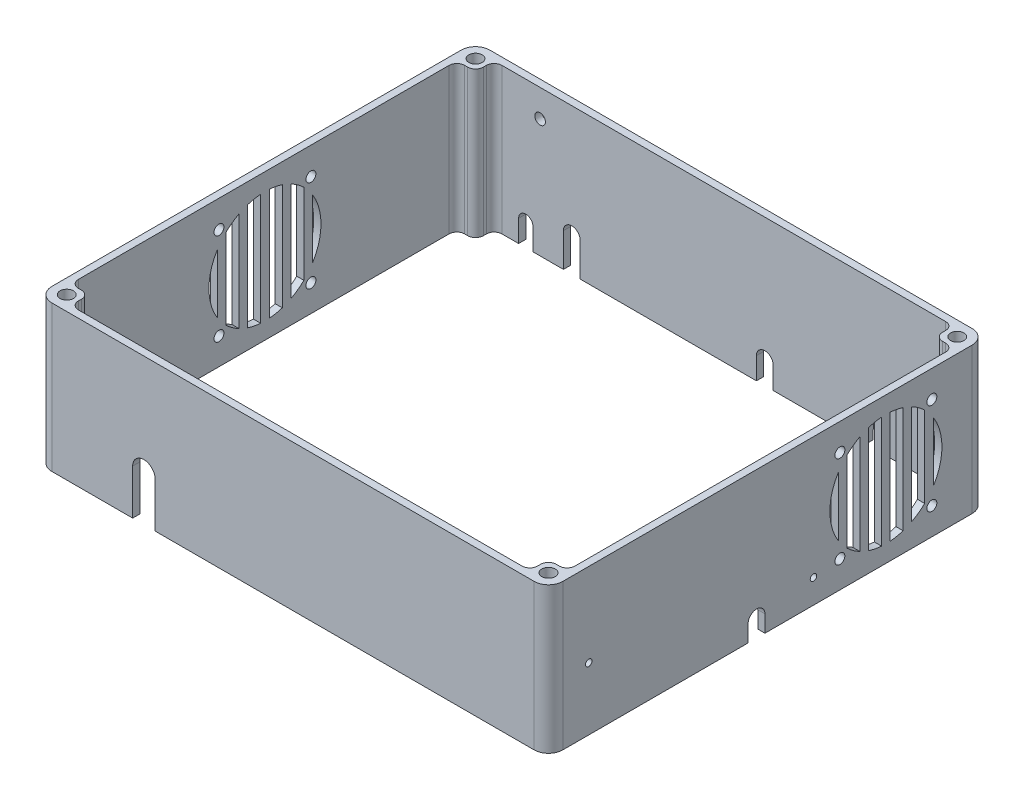
SolidWorks part; units mm, degrees
other "Markup1"
sketch "Sketch20" plane through (177.8, 5.08, 6.35) normal (0.2164, -0.9756, 0.0368) x (0.7593, 0.1445, -0.6344)
material "ABS"
ref_plane "Front Plane" through (0, 0, 0) normal (0, 0, 1) x (1, 0, 0)
ref_plane "Top Plane" through (0, 0, 0) normal (0, 1, 0) x (1, 0, 0)
ref_plane "Right Plane" through (0, 0, 0) normal (1, 0, 0) x (0, 0, -1)
sketch "Sketch1" plane through (0, 0, 0) normal (0, 1, 0) x (1, 0, 0)
  line L2 (0, 0) -> (0, 146.05)
  line L3 (0, 146.05) -> (177.8, 146.05)
  line L4 (177.8, 0) -> (177.8, 146.05)
  line L6 (0, 0) -> (0, -6.35)
  line L7 (0, -6.35) -> (177.8, -6.35)
  line L8 (177.8, 0) -> (177.8, -6.35)
  dimension "D1" = 146.05
  dimension "D2" = 177.8
  dimension "D3" = 6.35
extrude "Boss-Extrude1" add sketch "Sketch1" along normal blind 55.88 contours L2 L3 L4 L8 L7 L6
shell "Shell1" thickness 2.5
sketch "Sketch3" plane through (0, 55.88, 0) normal (0, 1, 0) x (1, 0, 0)
  line L1 (2.5, 143.55) -> (9, 143.55)
  line L2 (2.5, 143.55) -> (2.5, 137.05)
  line L3 (2.5, 137.05) -> (9, 137.05)
  line L4 (9, 143.55) -> (9, 137.05)
  line L5 (175.3, 143.55) -> (168.8, 143.55)
  line L6 (175.3, 143.55) -> (175.3, 137.05)
  line L7 (175.3, 137.05) -> (168.8, 137.05)
  line L8 (168.8, 143.55) -> (168.8, 137.05)
  line L9 (175.3, -3.85) -> (168.8, -3.85)
  line L10 (175.3, -3.85) -> (175.3, 2.65)
  line L11 (175.3, 2.65) -> (168.8, 2.65)
  line L12 (168.8, -3.85) -> (168.8, 2.65)
  line L13 (2.5, -3.85) -> (9, -3.85)
  line L14 (2.5, -3.85) -> (2.5, 2.65)
  line L15 (2.5, 2.65) -> (9, 2.65)
  line L16 (9, -3.85) -> (9, 2.65)
  line L19 (2.5, -3.85) -> (175.3, -3.85) construction
  dimension "D1" = 6.5
  dimension "D2" = 6.5
extrude "Boss-Extrude2" add sketch "Sketch3" against normal up to surface (53.38 mm away) up to face at (88.9, 2.5, -69.85)
sketch "pi&pcbSketch"
  dimension "D1" = 58
  dimension "D2" = 48.9998
  dimension "D3" = 4.826
  dimension "D4" = 12.192
  dimension "D5" = 4.6482
  dimension "D6" = 4.826
  dimension "D7" = 3.0734
  dimension "D8" = 12.954
  dimension "D9" = 13.8684
sketch "bottomHoleSketch" [suppressed] plane through (0, 0, -5.08) normal (0, 1, 0) x (-1, 0, 0)
  line L0 (0, -140.97) -> (-177.8, -140.97) construction
  line L1 (-177.8, -140.97) -> (-177.8, 11.43) construction
  line L2 (0, 11.43) -> (-177.8, 11.43) construction
  line L3 (0, -140.97) -> (0, 11.43) construction
  circle A0 centre (-172.72, 6.35) radius 2.5249
  circle A1 centre (-5.08, 6.35) radius 2.5249
  circle A2 centre (-172.72, -135.89) radius 2.5249
  circle A3 centre (-5.08, -135.89) radius 2.5249
  dimension "D3" = 5.0497
  dimension "D1" = 5.08
  dimension "D2" = 5.08
  dimension "D4" = 5.08
  dimension "D5" = 5.08
sketch "Sketch35" plane through (0, 55.88, -60.96) normal (0, 1, 0) x (-1, 0, 0)
  line L0 (-177.8, -85.09) -> (-177.8, 67.31) construction
  line L1 (0, 67.31) -> (-177.8, 67.31) construction
  line L2 (0, -85.09) -> (0, 67.31) construction
  line L3 (0, -85.09) -> (-177.8, -85.09) construction
  circle A0 centre (-172.72, 62.23) radius 2.325
  circle A1 centre (-5.08, 62.23) radius 2.325
  circle A2 centre (-172.72, -80.01) radius 2.325
  circle A3 centre (-5.08, -80.01) radius 2.325
  dimension "D3" = 4.65
  dimension "D1" = 5.08
  dimension "D2" = 5.08
  dimension "D4" = 5.08
  dimension "D5" = 5.08
extrude "Top holes" cut sketch "Sketch35" against normal blind 10
sketch "Ethernet" plane through (0, 2.5, 0) normal (0, 1, 0) x (1, 0, 0)
  line L1 (132.4077, 54.1476) -> (157.8077, 54.1476)
  line L2 (132.4077, 54.1476) -> (132.4077, 38.2816)
  line L3 (132.4077, 38.2816) -> (157.8077, 38.2816)
  line L4 (157.8077, 54.1476) -> (157.8077, 38.2816)
  dimension "D1" = 25.4
extrude "Ether" [suppressed] add sketch "Ethernet" along normal blind 10.16 separate body
sketch "Sketch9" [suppressed] plane through (0, 0, 6.35) normal (0, 0, 1) x (1, 0, 0)
  line L1 (0, 2.5) -> (177.8, 2.5)
  line L2 (0, 2.5) -> (0, 55.88)
  line L3 (0, 55.88) -> (177.8, 55.88)
  line L4 (177.8, 2.5) -> (177.8, 55.88)
  line L6 (0, 0) -> (177.8, 0) construction
  line L7 (177.8, 55.88) -> (177.8, 0) construction
  line L8 (0, 55.88) -> (0, 0) construction
  dimension "D1" = 2.5
extrude "Cut Top Off" [suppressed] cut sketch "Sketch9" against normal through all
sketch "Sketch7" plane through (0, 2.5, 0) normal (0, 1, 0) x (1, 0, 0)
  circle A0 centre (48.9094, 40.0026) radius 3
  circle A1 centre (106.9094, 40.0026) radius 3
  circle A3 centre (106.9094, 89.0026) radius 3
  circle A4 centre (48.9094, 89.0026) radius 3
  dimension "D1" = 6
  dimension "D4" = 49
  dimension "D2" = 58
extrude "Standoff" [suppressed] add sketch "Sketch7" along normal blind 5
sketch "Sketch10" plane through (0, 0, 6.35) normal (0, 0, 1) x (1, 0, 0)
  line L1 (0, 0) -> (177.8, 0)
  line L2 (0, 0) -> (0, 5.08)
  line L3 (0, 5.08) -> (177.8, 5.08)
  line L4 (177.8, 0) -> (177.8, 5.08)
  dimension "D1" = 5.08
extrude "cut Bottom off" cut sketch "Sketch10" against normal through all
sketch "Sketch17" plane through (0, 5.08, 5.08) normal (0, 1, 0) x (1, 0, 0)
  line L4 (0, 151.13) -> (0, -1.27) construction
  line L5 (0, 151.13) -> (177.8, 151.13) construction
  line L6 (0, -1.27) -> (177.8, -1.27) construction
  line L7 (177.8, 151.13) -> (177.8, -1.27) construction
  circle A0 centre (5.08, 146.05) radius 2.325
  circle A1 centre (172.72, 146.05) radius 2.325
  circle A2 centre (5.08, 3.81) radius 2.325
  circle A3 centre (172.72, 3.81) radius 2.325
  dimension "D3" = 4.65
  dimension "D1" = 5.08
  dimension "D2" = 5.08
  dimension "D4" = 5.08
  dimension "D5" = 5.08
extrude "Bottom of Top holes" cut sketch "Sketch17" along normal blind 10
sketch "Sketch12" plane through (299.72, 0, -143.55) normal (0, 0, 1) x (1, 0, 0)
  line L0 (-121.92, 5.08) -> (-299.72, 5.08) construction
  line L1 (-130.92, 5.08) -> (-130.92, 55.88) construction
  line L2 (-155.3866, 11.684) -> (-155.3866, 5.08)
  line L3 (-155.3866, 5.08) -> (-161.3866, 5.08)
  line L4 (-161.3866, 5.08) -> (-161.2278, 11.7535)
  arc A1 (-155.3866, 11.684) -> (-161.2278, 11.7535) centre (-158.3076, 11.684) ccw
  dimension "D2" = 6.604
  dimension "D1" = 2.921
  dimension "D3" = 24.4666
  dimension "D4" = 6
extrude "cut for Ethernet Cable" cut sketch "Sketch12" against normal up to next
sketch "Sketch15" plane through (0, 0, 3.85) normal (0, 0, -1) x (-1, 0, 0)
  line L0 (-23.749, 10.922) -> (-23.749, 5.08)
  line L1 (-23.749, 5.08) -> (-29.591, 5.08)
  line L2 (-29.591, 5.08) -> (-29.591, 10.922)
  arc A0 (-23.749, 10.922) -> (-29.591, 10.922) centre (-26.67, 10.922) ccw
  dimension "D2" = 2.921
  dimension "D1" = 5.842
  dimension "D3" = 5.842
extrude "usbA" [suppressed] cut sketch "Sketch15" against normal up to next
sketch "Sketch16" plane through (175.3, 0, 0) normal (-1, 0, 0) x (0, 0, 1)
  line L0 (-63.129, 10.922) -> (-63.129, 5.08)
  line L1 (-63.129, 5.08) -> (-68.971, 5.08)
  line L2 (-68.971, 5.08) -> (-68.971, 10.922)
  line L3 (-2.65, 5.08) -> (-137.05, 5.08) construction
  line L4 (-146.05, 55.88) -> (-146.05, 5.08) construction
  arc A0 (-63.129, 10.922) -> (-68.971, 10.922) centre (-66.05, 10.922) ccw
  dimension "D2" = 2.921
  dimension "D1" = 5.842
  dimension "D3" = 5.842
  dimension "D4" = 80
extrude "Keycard" cut sketch "Sketch16" against normal up to next
fillet "Fillet1" radius 2.7 12 edges at (9, 30.48, -2.65) (168.8, 30.48, -2.65) (168.8, 30.48, -137.05) (9, 30.48, -137.05) (2.5, 30.48, -137.05) (9, 30.48, -143.55) (2.5, 30.48, -2.65) (9, 30.48, 3.85) (168.8, 30.48, 3.85) (175.3, 30.48, -2.65) (175.3, 30.48, -137.05) (168.8, 30.48, -143.55)
sketch "Sketch13" plane through (0, 0, -143.55) normal (0, 0, 1) x (1, 0, 0)
  line L4 (106.1, 12.7) -> (106.1, 5.08)
  line L5 (38.9387, 16.76) -> (38.9387, 5.08)
  line L6 (38.9387, 5.08) -> (33.0967, 5.08)
  line L7 (33.0967, 5.08) -> (33.0967, 16.76)
  line L8 (11.7, 5.08) -> (138.3334, 5.08) construction
  line L9 (106.1, 5.08) -> (100.258, 5.08)
  line L10 (177.8, 55.88) -> (177.8, 5.08) construction
  line L12 (100.258, 5.08) -> (100.258, 12.7)
  line L13 (22.5, 12.7) -> (22.5, 5.08)
  line L14 (22.5, 5.08) -> (17.5, 5.08)
  line L15 (17.5, 5.08) -> (17.5, 12.7)
  line L16 (0, 55.88) -> (0, 5.08) construction
  line L17 (11.7, 5.08) -> (138.3334, 5.08) construction
  arc A1 (38.9387, 16.76) -> (33.0967, 16.76) centre (36.0177, 16.76) ccw
  arc A2 (106.1, 12.7) -> (100.258, 12.7) centre (103.179, 12.7) ccw
  arc A3 (22.5, 12.7) -> (17.5, 12.7) centre (20, 12.7) ccw
  dimension "D5" = 2.921
  dimension "D10" = 2.921
  dimension "D12" = 2.5
  dimension "D4" = 5.842
  dimension "D6" = 11.68
  dimension "D8" = 36.0177
  dimension "D9" = 5.842
  dimension "D11" = 5
  dimension "D13" = 7.62
  dimension "D14" = 20
  dimension "D15" = 7.62
  dimension "D16" = 74.621
extrude "usb B" cut sketch "Sketch13" against normal up to next
sketch "Sketch23" plane through (177.8, 0, -323.85) normal (-1, 0, 0) x (0, 0, 1)
  line L89 (177.8, 55.88) -> (177.8, 5.08) construction
  line L121 (177.8, 30.48) -> (212.8, 30.48) construction
  line L122 (221.8251, 11.0378) -> (221.8251, 49.9222)
  line L123 (214.3, 11.0378) -> (211.3, 11.0378)
  line L124 (214.3, 11.0378) -> (214.3, 49.9222)
  line L125 (214.3, 49.9222) -> (211.3, 49.9222)
  line L126 (211.3, 11.0378) -> (211.3, 49.9222)
  line L127 (221.8251, 11.0378) -> (218.8251, 11.0378)
  line L128 (218.8251, 11.0378) -> (218.8251, 49.9222)
  line L129 (221.8251, 49.9222) -> (218.8251, 49.9222)
  line L130 (229.3502, 11.0378) -> (229.3502, 49.9222)
  line L131 (229.3502, 11.0378) -> (226.3502, 11.0378)
  line L132 (226.3502, 11.0378) -> (226.3502, 49.9222)
  line L133 (229.3502, 49.9222) -> (226.3502, 49.9222)
  line L134 (206.8, 11.0378) -> (206.8, 49.9222)
  line L136 (206.8, 11.0378) -> (203.8, 11.0378)
  line L138 (203.8, 11.0378) -> (203.8, 49.9222)
  line L140 (206.8, 49.9222) -> (203.8, 49.9222)
  line L142 (199.3, 11.0378) -> (199.3, 49.9222)
  line L144 (199.3, 11.0378) -> (196.3, 11.0378)
  line L146 (196.3, 11.0378) -> (196.3, 49.9222)
  line L148 (199.3, 49.9222) -> (196.3, 49.9222)
  circle A0 centre (212.8, 30.48) radius 19.5
  circle A1 centre (196.8, 46.48) radius 1.73
  circle A2 centre (228.8, 46.48) radius 1.73
  circle A3 centre (228.8, 14.48) radius 1.73
  circle A4 centre (196.8, 14.48) radius 1.73
  point P87 (212.8, 30.48)
  dimension "D4" = 3
  dimension "D2" = 3
  dimension "D12" = 3.46
  dimension "D14" = 39
  dimension "D15" = 35
  dimension "D3" = 1.5
  dimension "D5" = 3
  dimension "D10" = 16
  dimension "D11" = 16
  dimension "D13" = 4
fillet "Fillet2" radius 5 4 edges at (0, 30.48, -146.05) (177.8, 30.48, 6.35) (0, 30.48, 6.35) (177.8, 30.48, -146.05)
extrude "RightFan" cut sketch "Sketch23" along normal blind 10 contours L134 L121 L126 A0 | L121 L134 A0 L126 | L121 L142 A0 L138 | L142 L121 L138 A0 | L121 A0 L146 | A0 L121 L146 | A0 L124 L128 | A0 L122 L132 | A0 L130 | A4 | A3 | A2 | A1
sketch "Sketch36" plane through (0, 0, 323.85) normal (1, 0, 0) x (0, 0, -1)
  line L121 (294.149, 30.3772) -> (394.1302, 30.3772) construction
  line L122 (403.1553, 10.935) -> (403.1553, 49.8194)
  line L123 (395.6302, 10.935) -> (392.6302, 10.935)
  line L124 (395.6302, 10.935) -> (395.6302, 49.8194)
  line L125 (395.6302, 49.8194) -> (392.6302, 49.8194)
  line L126 (392.6302, 10.935) -> (392.6302, 49.8194)
  line L127 (403.1553, 10.935) -> (400.1553, 10.935)
  line L128 (400.1553, 10.935) -> (400.1553, 49.8194)
  line L129 (403.1553, 49.8194) -> (400.1553, 49.8194)
  line L130 (410.6804, 10.935) -> (410.6804, 49.8194)
  line L131 (410.6804, 10.935) -> (407.6804, 10.935)
  line L132 (407.6804, 10.935) -> (407.6804, 49.8194)
  line L133 (410.6804, 49.8194) -> (407.6804, 49.8194)
  line L134 (388.1302, 10.935) -> (388.1302, 49.8194)
  line L136 (388.1302, 10.935) -> (385.1302, 10.935)
  line L137 (464.9, 55.88) -> (464.9, 5.08) construction
  line L138 (385.1302, 10.935) -> (385.1302, 49.8194)
  line L139 (464.9, 5.08) -> (322.5, 5.08) construction
  line L140 (388.1302, 49.8194) -> (385.1302, 49.8194)
  line L142 (380.6302, 10.935) -> (380.6302, 49.8194)
  line L144 (380.6302, 10.935) -> (377.6302, 10.935)
  line L146 (377.6302, 10.935) -> (377.6302, 49.8194)
  line L148 (380.6302, 49.8194) -> (377.6302, 49.8194)
  circle A0 centre (394.1302, 30.3772) radius 19.5
  circle A1 centre (378.1302, 46.3772) radius 1.73
  circle A2 centre (410.1302, 46.3772) radius 1.73
  circle A3 centre (410.1302, 14.3772) radius 1.73
  circle A4 centre (378.1302, 14.3772) radius 1.73
  point P87 (394.1302, 30.3772)
  dimension "D4" = 3
  dimension "D2" = 3
  dimension "D12" = 3.46
  dimension "D14" = 39
  dimension "D3" = 1.5
  dimension "D5" = 3
  dimension "D6" = 70.7698
  dimension "D7" = 25.2972
  dimension "D10" = 16
  dimension "D11" = 16
  dimension "D13" = 4
hole_wizard "CSK for M3 Flat Head Machine Screw4" [suppressed] positions "3DSketch10" profile "Sketch34" countersink size "M3" standard "ANSI Metric"
sketch3d "3DSketch10"
  point P0 (5.08, 0, 1.27)
  point P3 (172.72, 0, 1.27)
  point P6 (172.72, 0, -140.97)
  point P9 (5.08, 0, -140.97)
sketch "Sketch34" plane through (5.08, 0, 1.27) normal (1, 0, 0) x (0, 0, -1)
  line L0 (0, 0) -> (0, 11.0215)
  line L1 (0, 11.0215) -> (1.7, 10)
  line L2 (1.7, 10) -> (1.7, 1.45)
  line L3 (1.7, 1.45) -> (3.15, 0)
  line L5 (3.15, 0) -> (0, 0)
  line L6 (-1.7, 1.45) -> (-3.15, 0) construction
  line L10 (0, 11.0215) -> (-1.7, 10) construction
  line L11 (0, -6.35) -> (0, 107.95) construction
  dimension "Hole Dia." = 3.4
  dimension "Hole Depth" = 10
  dimension "Near C'Sink Dia." = 6.3
  dimension "Near C'Sink Angle" = 90
  dimension "Drill Angle" = 118
extrude "Cut-Extrude1" cut sketch "Sketch36" along normal blind 10 contours L122 L121 L132 A0 | L130 L121 A0 | L121 L130 A0 | L121 L122 A0 L132 | L121 L124 A0 L128 | L124 L121 L128 A0 | L134 L121 L126 A0 | L121 L134 A0 L126 | L121 L142 A0 L138 | L142 L121 L138 A0 | A0 L121 L146 | L121 A0 L146 | A4 | A1 | A2 | A3
sketch "Sketch37" [suppressed] plane through (0, 0, 0) normal (0, 1, 0) x (1, 0, 0)
  circle A0 centre (48.9094, 40.0026) radius 1.3
  circle A2 centre (106.9094, 89.0026) radius 1.3
  circle A3 centre (106.9094, 40.0026) radius 1.3
  circle A4 centre (48.9094, 89.0026) radius 1.3
  dimension "D1" = 2.6
hole_wizard "CBORE for M2.5 Pan Head Machine Screw3" [suppressed] positions "3DSketch13" profile "Sketch41" counterbore size "M2.5" standard "ANSI Metric"
sketch3d "3DSketch13"
  point P0 (106.9094, 0, -89.0026)
  point P8 (48.9094, 0, -40.0026)
  point P16 (48.9094, 0, -40.0026)
  point P53 (48.9094, 0, -89.0026)
  point P56 (106.9094, 0, -40.0026)
sketch "Sketch41" plane through (106.9094, 0, -89.0026) normal (1, 0, 0) x (0, 0, -1)
  line L0 (0, 0) -> (0, 10.8712)
  line L1 (0, 10.8712) -> (1.45, 10)
  line L2 (1.45, 10) -> (1.45, 2.1)
  line L3 (1.45, 2.1) -> (3, 2.1)
  line L4 (3, 2.1) -> (3, 0)
  line L5 (3, 0) -> (0, 0)
  line L10 (0, 10.8712) -> (-1.45, 10) construction
  line L11 (0, -6.35) -> (0, 107.95) construction
  dimension "Hole Dia." = 2.9
  dimension "Hole Depth" = 10
  dimension "C'Bore Dia." = 6
  dimension "C'Bore Depth" = 2.1
  dimension "Drill Angle" = 118
fillet "Fillet3" [suppressed] radius 1
sketch "Sketch42" plane through (0, 0, -146.05) normal (0, 0, -1) x (-1, 0, 0)
  line L0 (0, 59.265) -> (0, 55.88) construction
  line L1 (-5, 55.88) -> (-172.8, 55.88) construction
  circle A2 centre (-24.9828, 46.375) radius 1.85
  dimension "D1" = 24.9828
  dimension "D2" = 9.505
extrude "Cut-Extrude2" cut sketch "Sketch42" against normal up to next
sketch "Sketch43" plane through (0, 0, 6.35) normal (0, 0, 1) x (1, 0, 0)
  line L0 (172.8, 5.08) -> (5, 5.08) construction
  line L2 (40.8967, 5.08) -> (40.8967, 20.78)
  line L3 (33.0967, 20.78) -> (33.0967, 5.08)
  line L4 (33.0967, 5.08) -> (40.8967, 5.08)
  arc A1 (40.8967, 20.78) -> (33.0967, 20.78) centre (36.9967, 20.78) ccw
  point P8 (36.9967, 24.68)
  point P9 (40.0785, 5.08)
  point P10 (0, 0)
  point P11 (0, 0)
  point P12 (40.1519, 22.4431)
  point P13 (0, 0)
  point P14 (40.8967, 20.78)
  point P15 (40.8967, 20.78)
  point P16 (0, 0)
  dimension "D2" = 3.9
  dimension "D1" = 19.6
  dimension "D3" = 33.0967
  dimension "D4" = 7.8
extrude "Cut-Extrude3" cut sketch "Sketch43" against normal up to next
sketch "Sketch44" plane through (177.8, 0, 0) normal (1, 0, 0) x (0, 0, -1)
  line L0 (141.05, 5.08) -> (68.971, 5.08) construction
  line L1 (63.129, 5.08) -> (-1.35, 5.08) construction
  line L2 (-6.35, 5.08) -> (-6.35, 55.88) construction
  circle A0 centre (7.65, 26.83) radius 1.675
  circle A1 centre (85.8604, 13.43) radius 1.675
  point P4 (80.9664, 13.0238)
  dimension "D2" = 21.75
  dimension "D5" = 3.35
  dimension "D1" = 8.35
  dimension "D3" = 14
  dimension "D4" = 79.35
hole_wizard "Tap Drill for #4-40 Tap1" positions "3DSketch14" profile "Sketch46" hole size "#4-40" standard "ANSI Inch"
sketch3d "3DSketch14"
  point P0 (177.8, 26.83, -7.65)
  point P3 (177.8, 13.43, -85.8604)
sketch "Sketch46" plane through (177.8, 26.83, -7.65) normal (0, 1, 0) x (0, 0, -1)
  line L0 (0, 0) -> (0, 2.5)
  line L1 (0, 2.5) -> (1.1303, 2.5)
  line L2 (1.1303, 2.5) -> (1.1303, 0)
  line L5 (1.1303, 0) -> (0, 0)
  line L11 (0, -6.35) -> (0, 107.95) construction
  dimension "Thru Hole Dia." = 2.2606
  dimension "Thru Hole Depth" = 2.5
